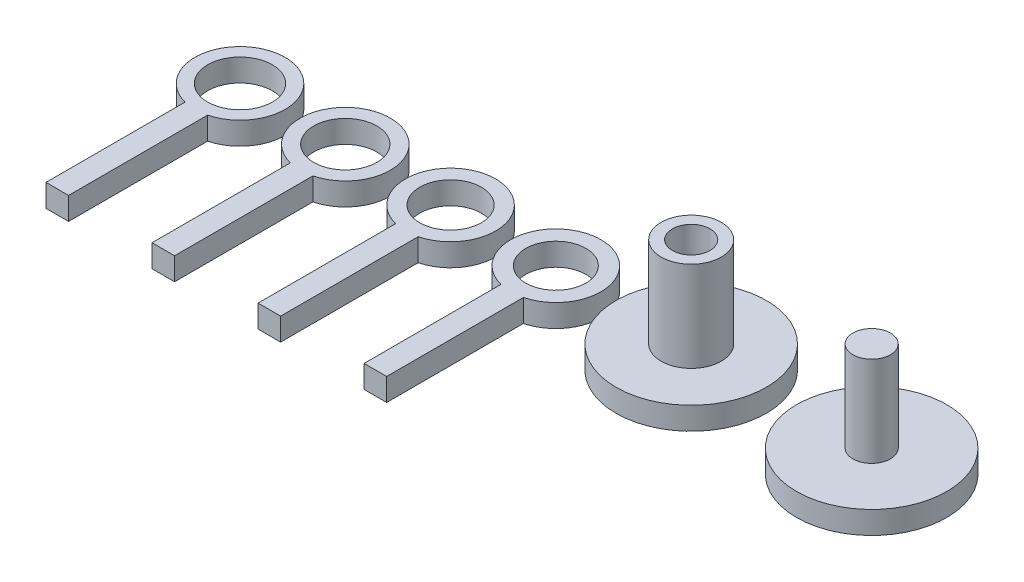
SolidWorks part; units mm, degrees
ref_plane "Спереди" through (0, 0, 0) normal (0, 0, 1) x (1, 0, 0)
ref_plane "Сверху" through (0, 0, 0) normal (0, 1, 0) x (1, 0, 0)
ref_plane "Справа" through (0, 0, 0) normal (1, 0, 0) x (0, 0, -1)
other "Configuration Table"
sketch "Эскиз1" plane through (0, 0, 0) normal (0, 1, 0) x (1, 0, 0)
  line L1 (0, 0) -> (24, 0) construction
  circle A0 centre (0, 0) radius 10
  circle A1 centre (24, 0) radius 10
  dimension "D1" = 20
  dimension "D2" = 20
  dimension "D3" = 24
extrude "Бобышка-Вытянуть1" add sketch "Эскиз1" along normal blind 3
sketch "Эскиз3" plane through (0, 3, 0) normal (0, 1, 0) x (1, 0, 0)
  circle A0 centre (0, 0) radius 4
  circle A1 centre (0, 0) radius 2.5
  dimension "D1" = 8
  dimension "D2" = 5
sketch "Эскиз4" plane through (0, 3, 0) normal (0, 1, 0) x (1, 0, 0)
  circle A0 centre (24, 0) radius 2.5
  dimension "D1" = 5
extrude "Бобышка-Вытянуть2" add sketch "Эскиз4" along normal blind 12
extrude "Бобышка-Вытянуть3" add sketch "Эскиз3" along normal blind 12
sketch "Эскиз5" plane through (0, 0, 0) normal (0, 1, 0) x (1, 0, 0)
  line L0 (0, 0) -> (-18, 0) construction
  line L1 (-18, 0) -> (-32, 0) construction
  line L2 (-32, 0) -> (-46, 0) construction
  line L3 (-46, 0) -> (-60, 0) construction
  line L4 (-60, -4.3) -> (-60, -14.3) construction
  line L5 (-46, -4.2) -> (-46, -14.2) construction
  line L6 (-32, -4.1) -> (-32, -14.1) construction
  line L7 (-18, -4) -> (-18, -14) construction
  line L8 (-61.5, -4.3) -> (-61.5, -5.8095) construction
  line L9 (-61.5, -24.3) -> (-58.5, -24.3)
  line L10 (-61.5, -24.3) -> (-61.5, -5.8095)
  line L12 (-58.5, -24.3) -> (-58.5, -5.8095)
  line L13 (-61.5, -24.3) -> (-58.5, -4.3) construction
  line L14 (-61.5, -4.3) -> (-58.5, -24.3) construction
  line L15 (-47.5, -24.2) -> (-44.5, -24.2)
  line L16 (-47.5, -24.2) -> (-47.5, -5.8095)
  line L18 (-44.5, -24.2) -> (-44.5, -5.8095)
  line L19 (-47.5, -24.2) -> (-44.5, -4.2) construction
  line L20 (-47.5, -4.2) -> (-44.5, -24.2) construction
  line L21 (-33.5, -24.1) -> (-30.5, -24.1)
  line L22 (-33.5, -24.1) -> (-33.5, -5.8095)
  line L24 (-30.5, -24.1) -> (-30.5, -5.8095)
  line L25 (-33.5, -24.1) -> (-30.5, -4.1) construction
  line L26 (-33.5, -4.1) -> (-30.5, -24.1) construction
  line L27 (-19.5, -24) -> (-16.5, -24)
  line L28 (-19.5, -24) -> (-19.5, -5.8095)
  line L30 (-16.5, -24) -> (-16.5, -5.8095)
  line L31 (-19.5, -24) -> (-16.5, -4) construction
  line L32 (-19.5, -4) -> (-16.5, -24) construction
  line L33 (-61.5, -5.8095) -> (-58.5, -5.8095) construction
  line L34 (-58.5, -5.8095) -> (-58.5, -4.3) construction
  line L35 (-47.5, -4.2) -> (-47.5, -5.8095) construction
  line L36 (-44.5, -5.8095) -> (-44.5, -4.2) construction
  line L37 (-44.5, -4.2) -> (-47.5, -4.2) construction
  line L38 (-61.5, -4.3) -> (-60, -4.3) construction
  line L39 (-60, -4.3) -> (-58.5, -4.3) construction
  line L40 (-47.5, -5.8095) -> (-44.5, -5.8095) construction
  line L41 (-47.5, -4.2) -> (-46, -4.2) construction
  line L42 (-33.5, -5.8095) -> (-33.5, -4.1) construction
  line L43 (-33.5, -4.1) -> (-32, -4.1) construction
  line L44 (-32, -4.1) -> (-30.5, -4.1) construction
  line L45 (-30.5, -4.1) -> (-30.5, -5.8095) construction
  line L46 (-33.5, -5.8095) -> (-30.5, -5.8095) construction
  line L47 (-19.5, -5.8095) -> (-16.5, -5.8095) construction
  line L48 (-16.5, -4) -> (-18, -4) construction
  line L49 (-18, -4) -> (-19.5, -4) construction
  line L50 (-19.5, -4) -> (-19.5, -5.8095) construction
  line L51 (-16.5, -5.8095) -> (-16.5, -4) construction
  circle A0 centre (-18, 0) radius 4
  arc A1 (-16.5, -5.8095) -> (-19.5, -5.8095) centre (-18, 0) ccw
  circle A2 centre (-32, 0) radius 4.1
  arc A3 (-30.5, -5.8095) -> (-33.5, -5.8095) centre (-32, 0) ccw
  arc A4 (-58.5, -5.8095) -> (-61.5, -5.8095) centre (-60, 0) ccw
  circle A5 centre (-60, 0) radius 4.3
  arc A6 (-44.5, -5.8095) -> (-47.5, -5.8095) centre (-46, 0) ccw
  circle A7 centre (-46, 0) radius 4.2
  dimension "D1" = 18
  dimension "D2" = 14
  dimension "D5" = 8
  dimension "D6" = 8.2
  dimension "D7" = 8.4
  dimension "D8" = 8.6
  dimension "D9" = 12
  dimension "D10" = 12
  dimension "D11" = 12
  dimension "D12" = 12
  dimension "D3" = 14
  dimension "D4" = 14
  dimension "D13" = 10
  dimension "D14" = 10
  dimension "D15" = 10
  dimension "D16" = 10
  dimension "D17" = 3
  dimension "D18" = 3
  dimension "D19" = 3
  dimension "D20" = 3
extrude "Бобышка-Вытянуть4" add sketch "Эскиз5" along normal blind 3 separate body
